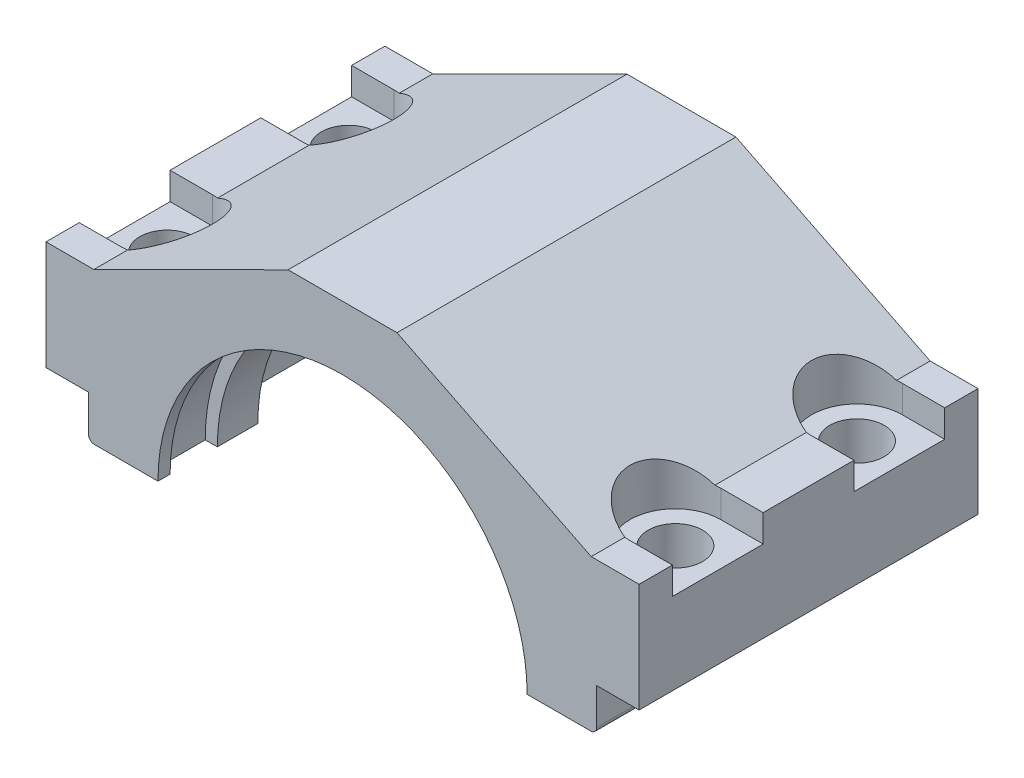
SolidWorks part; units mm, degrees
ref_plane "Front Plane" through (0, 0, 0) normal (0, 0, 1) x (1, 0, 0)
ref_plane "Top Plane" through (0, 0, 0) normal (0, 1, 0) x (1, 0, 0)
ref_plane "Right Plane" through (0, 0, 0) normal (1, 0, 0) x (0, 0, -1)
sketch "Sketch1" plane through (0, 0, 0) normal (0, 0, 1) x (1, 0, 0)
  line L0 (-30.5, 0) -> (-41, 0)
  line L1 (-42, 1) -> (-42, 7)
  line L2 (-42, 7) -> (-49, 7)
  line L3 (-49, 7) -> (-49, 25)
  line L4 (-49, 25) -> (-41.09, 25)
  line L5 (-41.09, 25) -> (-9, 41)
  line L6 (-9, 41) -> (0, 41)
  line L7 (0, 41) -> (0, 30.5)
  arc A0 (0, 30.5) -> (-30.5, 0) centre (0, 0) ccw
  arc A1 (-41, 0) -> (-42, 1) centre (-41, 1) cw
  point P13 (0, 0)
  point P14 (0, 0)
  point P15 (0, 0)
  point P16 (0, 0)
  dimension "D1" = 1
  dimension "D3" = 30.5
  dimension "D2" = 7
  dimension "D4" = 7
  dimension "D5" = 18
  dimension "D6" = 41
  dimension "D7" = 9
  dimension "D8" = 11.5
  dimension "D9" = 7.91
extrude "Boss-Extrude1" add sketch "Sketch1" against normal blind 56 contours L5 L6 L7 A0 L0 A1 L1 L2 L3 L4
sketch "Sketch2" plane through (0, 0, 0) normal (0, -1, 0) x (1, 0, 0)
  line L0 (-30.5, -2) -> (-32.5, -2)
  line L1 (-30.5, -56) -> (-30.5, 0) construction
  line L2 (-32.5, -2) -> (-32.5, -9.81)
  line L3 (-32.5, -9.81) -> (-30.5, -9.81)
  line L4 (-30.5, -9.81) -> (-30.5, -16.5)
  line L5 (-30.5, -16.5) -> (-36, -16.5)
  line L6 (-36, -16.5) -> (-36, -39.5)
  line L7 (-36, -39.5) -> (-30.5, -39.5)
  line L8 (-30.5, -39.5) -> (-30.5, -45)
  line L9 (-30.5, -45) -> (-32.497, -45)
  line L10 (-32.497, -45) -> (-32.497, -54)
  line L11 (-32.497, -54) -> (-30.5, -54)
  line L12 (-30.5, -54) -> (-30.5, -56)
  line L13 (-30.5, -56) -> (-30.5, 0)
  line L14 (-30.5, 0) -> (-41, 0) construction
  line L15 (-30.5, -56) -> (-41, -56) construction
  line L16 (0, 0) -> (0, -56) construction
  point P20 (-31.4985, -54)
  dimension "D1" = 7.81
  dimension "D2" = 2
  dimension "D3" = 23
  dimension "D4" = 9
  dimension "D5" = 2
  dimension "D6" = 6.69
  dimension "D7" = 2
  dimension "D8" = 5.5
  dimension "D9" = 1.997
revolve "Cut-Revolve6" cut sketch "Sketch2" about L16
sketch "Sketch4" plane through (0, 25, 0) normal (0, 1, 0) x (1, 0, 0)
  line L0 (-49, 50.5) -> (-42, 50.5)
  line L1 (-49, 56) -> (-49, 0) construction
  line L2 (-42, 35.5) -> (-49, 35.5)
  line L3 (-49, 56) -> (-41.09, 56) construction
  line L4 (-49, 50.5) -> (-49, 35.5)
  line L5 (-49, 20.5) -> (-42, 20.5)
  line L6 (-42, 5.5) -> (-49, 5.5)
  line L7 (-49, 20.5) -> (-49, 5.5)
  line L8 (-49, 0) -> (-41.09, 0) construction
  arc A0 (-42, 50.5) -> (-42, 35.5) centre (-42, 43) cw
  arc A1 (-42, 20.5) -> (-42, 5.5) centre (-42, 13) cw
  point P9 (0, 0)
  point P10 (0, 0)
  point P11 (0, 0)
  point P12 (0, 0)
  point P13 (0, 0)
  point P19 (-41.09, 21.3576)
  point P22 (0, 0)
  point P23 (0, 0)
  point P24 (0, 0)
  point P25 (-42.7127, 43)
  dimension "D2" = 7.5
  dimension "D5" = 7.5
  dimension "D1" = 7
  dimension "D3" = 13
  dimension "D6" = 13
extrude "Cut-Extrude1" cut sketch "Sketch4" along normal through all and the other way blind 4.5
sketch "Sketch5" plane through (0, 20.5, 0) normal (0, 1, 0) x (1, 0, 0)
  circle A0 centre (-42, 13) radius 4.5
  circle A1 centre (-42, 43) radius 4.5
  arc A2 (-41.09, 5.5554) -> (-41.09, 20.4446) centre (-42, 13) ccw construction
  arc A3 (-42, 35.5) -> (-42, 50.5) centre (-42, 43) ccw construction
  point P4 (-41.09, 43.4804)
  point P5 (-41.09, 12.1519)
  point P12 (0, 0)
  point P13 (0, 0)
  point P15 (0, 0)
  point P16 (0, 0)
  dimension "D1" = 9
  dimension "D2" = 9
extrude "Cut-Extrude2" cut sketch "Sketch5" against normal through all
mirror "Mirror1" about plane through (0, 41, -56) normal (-1, 0, 0) of bodies 104
